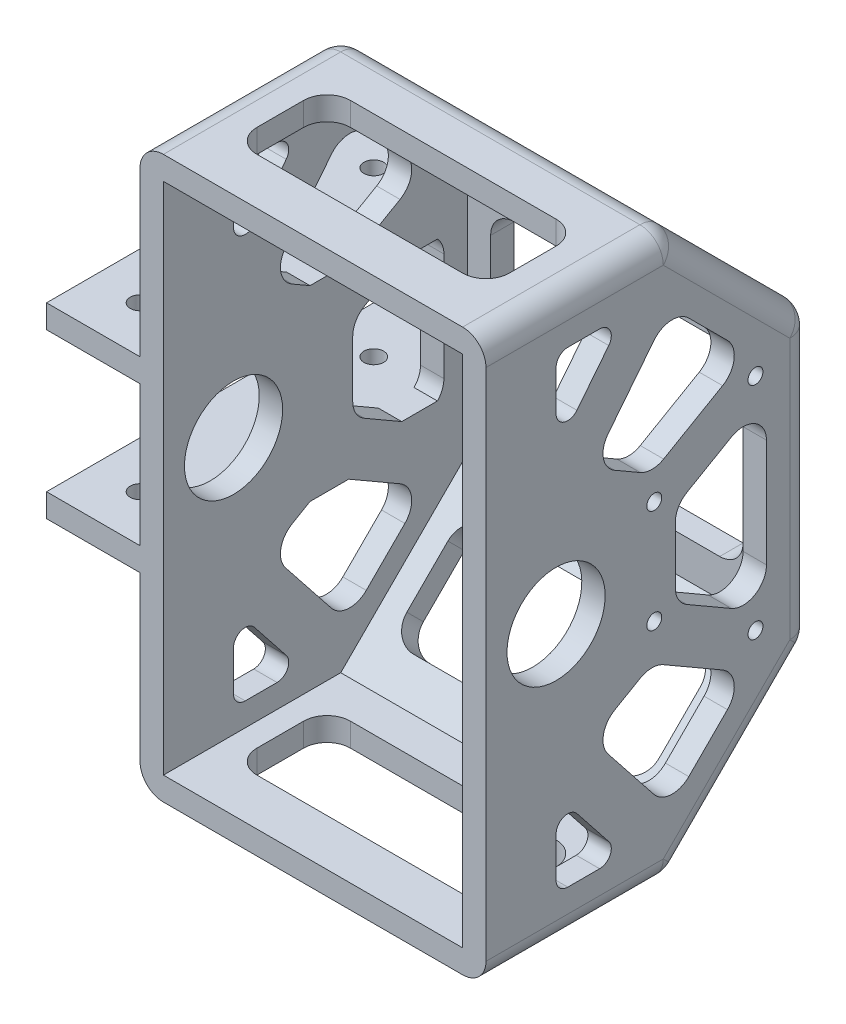
SolidWorks part; units mm, degrees
ref_plane "正面" through (0, 0, 0) normal (0, 0, 1) x (1, 0, 0)
ref_plane "平面" through (0, 0, 0) normal (0, 1, 0) x (1, 0, 0)
ref_plane "右側面" through (0, 0, 0) normal (1, 0, 0) x (0, 0, -1)
sketch "ｽｹｯﾁ1" plane through (0, 0, 0) normal (0, 0, 1) x (1, 0, 0)
  line L1 (-37, 60) -> (37, 60)
  line L2 (-37, 60) -> (-37, -60)
  line L3 (-37, -60) -> (37, -60)
  line L4 (37, 60) -> (37, -60)
  line L5 (-37, 60) -> (37, -60) construction
  line L6 (-37, -60) -> (37, 60) construction
  point P0 (0, 0)
  dimension "D1" = 120
  dimension "D2" = 74
extrude "ﾎﾞｽ - 押し出し1" add sketch "ｽｹｯﾁ1" along normal blind 70
chamfer "面取り2" distance 30 angle 45 2 edges at (0, 60, 0) (0, -60, 0)
sketch "ｽｹｯﾁ2" plane through (-37, 0, 0) normal (-1, 0, 0) x (0, 0, 1)
  line L0 (70, 60) -> (70, -60) construction
  line L1 (55, -23.6714) -> (55, -60)
  line L2 (55, 23.6714) -> (34.5, 11.8357)
  line L3 (34.5, 11.8357) -> (34.5, -11.8357)
  line L4 (34.5, -11.8357) -> (55, -23.6714)
  line L5 (55, -23.6714) -> (75.5, -11.8357)
  line L6 (75.5, -11.8357) -> (75.5, 11.8357)
  line L7 (75.5, 11.8357) -> (55, 23.6714)
  line L8 (70, -60) -> (30, -60) construction
  line L9 (34.5, -11.8357) -> (1.1122, -31.1122)
  line L11 (0, -30) -> (30, -60) construction
  line L12 (55, 23.6714) -> (55, 60)
  line L13 (70, 60) -> (30, 60) construction
  line L14 (34.5, 11.8357) -> (1.1122, 31.1122)
  line L15 (30, 60) -> (0, 30) construction
  line L16 (32, -16.1658) -> (52.5, -28.0015)
  line L17 (32, -7.5056) -> (-1.3878, -26.782)
  line L18 (57.5, -28.0015) -> (80.5, -14.7224)
  line L19 (80.5, -14.7224) -> (80.5, 14.7224)
  line L20 (80.5, 14.7224) -> (57.5, 28.0015)
  line L21 (29.5, 11.8357) -> (29.5, -11.8357)
  line L22 (37, 16.1658) -> (3.6122, 35.4423)
  line L23 (52.5, 28.0015) -> (32, 16.1658)
  line L24 (60, 23.6714) -> (60, 60)
  line L25 (60, -23.6714) -> (60, -60)
  line L26 (37, -7.5056) -> (57.5, -19.3412)
  line L27 (37, -16.1658) -> (3.6122, -35.4423)
  line L28 (52.5, -19.3412) -> (70.5, -8.9489)
  line L29 (70.5, -8.9489) -> (70.5, 8.9489)
  line L30 (70.5, 8.9489) -> (52.5, 19.3412)
  line L31 (39.5, 11.8357) -> (39.5, -11.8357)
  line L32 (32, 7.5056) -> (-1.3878, 26.782)
  line L33 (57.5, 19.3412) -> (37, 7.5056)
  line L35 (55, -23.6714) -> (34.1421, -50)
  line L36 (51.0808, -20.5665) -> (30.2229, -46.8952)
  line L37 (55, 23.6714) -> (34.1421, 50)
  line L38 (58.9192, 26.7762) -> (38.0613, 53.1048)
  line L39 (58.9192, -26.7762) -> (38.0613, -53.1048)
  line L40 (51.0808, 20.5665) -> (30.2229, 46.8952)
  line L47 (60, 50) -> (34.1421, 50)
  line L48 (34.1421, 50) -> (10, 25.8579)
  line L49 (10, 25.8579) -> (10, -25.8579)
  line L50 (10, -25.8579) -> (34.1421, -50)
  line L51 (34.1421, -50) -> (60, -50)
  line L52 (60, -50) -> (60, 50)
  line L53 (60, 50) -> (34.1421, 50)
  line L54 (34.1421, 50) -> (10, 25.8579)
  line L55 (10, 25.8579) -> (10, -25.8579)
  line L56 (10, -25.8579) -> (34.1421, -50)
  line L57 (34.1421, -50) -> (60, -50)
  line L58 (60, -50) -> (60, 50)
  circle A0 centre (55, 0) radius 10.5
  circle A1 centre (55, 0) radius 20.5 construction
  dimension "D1" = 21
  dimension "D2" = 15
  dimension "D3" = 41
  dimension "D4" = 5
  dimension "D5" = 5
  dimension "D6" = 10
  dimension "D7" = 5
  dimension "D8" = 5
shell "ｼｪﾙ1" thickness 5
extrude "ｶｯﾄ - 押し出し1" cut sketch "ｽｹｯﾁ2" against normal through all
sketch "ｽｹｯﾁ3" plane through (0, -15, -15) normal (0, -0.7071, -0.7071) x (1, 0, 0)
  line L8 (-27, 53.6396) -> (-27, 31.2132)
  line L9 (-27, 31.2132) -> (27, 31.2132)
  line L10 (27, 31.2132) -> (27, 53.6396)
  line L11 (27, 53.6396) -> (-27, 53.6396)
  line L12 (-27, 53.6396) -> (-27, 31.2132)
  line L13 (-27, 31.2132) -> (27, 31.2132)
  line L14 (27, 31.2132) -> (27, 53.6396)
  line L15 (27, 53.6396) -> (-27, 53.6396)
  dimension "D1" = 10
extrude "ｶｯﾄ - 押し出し2" cut sketch "ｽｹｯﾁ3" against normal blind 70
sketch "ｽｹｯﾁ4" plane through (0, 15, -15) normal (0, 0.7071, -0.7071) x (1, 0, 0)
  line L8 (27, -53.6396) -> (27, -31.2132)
  line L9 (27, -31.2132) -> (-27, -31.2132)
  line L10 (-27, -31.2132) -> (-27, -53.6396)
  line L11 (-27, -53.6396) -> (27, -53.6396)
  line L12 (27, -53.6396) -> (27, -31.2132)
  line L13 (27, -31.2132) -> (-27, -31.2132)
  line L14 (-27, -31.2132) -> (-27, -53.6396)
  line L15 (-27, -53.6396) -> (27, -53.6396)
  dimension "D1" = 10
extrude "ｶｯﾄ - 押し出し3" cut sketch "ｽｹｯﾁ4" against normal blind 70
sketch "ｽｹｯﾁ5" plane through (0, 0, 0) normal (0, 0, -1) x (-1, 0, 0)
  line L8 (27, -20) -> (27, 20)
  line L9 (27, 20) -> (-27, 20)
  line L10 (-27, 20) -> (-27, -20)
  line L11 (-27, -20) -> (27, -20)
  line L12 (27, -20) -> (27, 20)
  line L13 (27, 20) -> (-27, 20)
  line L14 (-27, 20) -> (-27, -20)
  line L15 (-27, -20) -> (27, -20)
  dimension "D1" = 10
extrude "ｶｯﾄ - 押し出し4" cut sketch "ｽｹｯﾁ5" against normal blind 70
sketch "ｽｹｯﾁ7" plane through (0, 60, 0) normal (0, 1, 0) x (1, 0, 0)
  line L8 (27, -60) -> (27, -40)
  line L9 (27, -40) -> (-27, -40)
  line L10 (-27, -40) -> (-27, -60)
  line L11 (-27, -60) -> (27, -60)
  line L12 (27, -60) -> (27, -40)
  line L13 (27, -40) -> (-27, -40)
  line L14 (-27, -40) -> (-27, -60)
  line L15 (-27, -60) -> (27, -60)
  dimension "D1" = 10
extrude "ｶｯﾄ - 押し出し5" cut sketch "ｽｹｯﾁ7" against normal through all
fillet "ﾌｨﾚｯﾄ1" radius 5 58 edges at (27, 51.1612, 24.6967) (-27, 51.1612, 24.6967) (-27, 35.3033, 8.8388) (27, 35.3033, 8.8388) (-27, 20, 2.5) (-27, -20, 2.5) (27, 20, 2.5) (27, -20, 2.5) (-27, -35.3033, 8.8388) (-27, -51.1612, 24.6967) (27, -51.1612, 24.6967) (27, -35.3033, 8.8388) (34.5, -29.596, 13.7382) (34.5, -17.6092, 34.5) (34.5, 17.6092, 34.5) (34.5, 29.596, 13.7382) (34.5, -20.2073, 10) (34.5, -8.9489, 29.5) (34.5, 8.9489, 29.5) (34.5, 20.2073, 10) (-34.5, 29.596, 13.7382) (-34.5, 17.6092, 34.5) (-34.5, 20.2073, 10) (-34.5, 8.9489, 29.5) (-34.5, -20.2073, 10) (-34.5, -8.9489, 29.5) (-34.5, -29.596, 13.7382) (-34.5, -17.6092, 34.5) (-27, -57.5, 60) (-27, -57.5, 40) (27, -57.5, 40) (27, -57.5, 60) (27, 57.5, 60) (27, 57.5, 40) (-27, 57.5, 40) (-27, 57.5, 60) (37, -45, 15) (37, -60, 50) (-37, -60, 50) (-37, -45, 15) (0, -30, 0) (-37, 0, 0) (-37, 45, 15) (0, 60, 30) (-37, 60, 50) (37, 60, 50) (0, 30, 0) (37, 45, 15) (37, 0, 0) (0, -60, 30) (34.5, -46.4408, 30.5829) (34.5, -25.1059, 47.4847) (34.5, 46.4408, 30.5829) (34.5, 25.1059, 47.4847) (-34.5, 46.4408, 30.5829) (-34.5, 25.1059, 47.4847) (-34.5, -25.1059, 47.4847) (-34.5, -46.4408, 30.5829)
sketch "ｽｹｯﾁ10" plane through (-37, 0, 0) normal (-1, 0, 0) x (0, 0, 1)
  line L0 (5, 27.9289) -> (5, -27.9289) construction
  line L1 (70, 17.5) -> (5, 17.5)
  line L2 (70, 17.5) -> (70, -17.5)
  line L3 (70, -17.5) -> (5, -17.5)
  line L4 (5, 17.5) -> (5, -17.5)
  line L5 (70, 17.5) -> (5, -17.5) construction
  line L6 (70, -17.5) -> (5, 17.5) construction
  line L7 (70, 55) -> (70, -55) construction
  line L8 (70, -15) -> (5, -15)
  line L9 (70, 20) -> (5, 20)
  line L10 (70, -20) -> (5, -20)
  line L11 (70, 15) -> (5, 15)
  line L13 (5, -15) -> (0, -15)
  line L14 (5, -15) -> (5, -20)
  line L15 (5, -20) -> (0, -20)
  line L16 (0, -15) -> (0, -20)
  line L17 (2.5, -20) -> (2.5, -15) construction
  line L18 (5, -17.5) -> (0, -17.5) construction
  line L19 (5, 20) -> (0, 20)
  line L20 (5, 20) -> (5, 15)
  line L21 (5, 15) -> (0, 15)
  line L22 (0, 20) -> (0, 15)
  line L23 (2.5, 15) -> (2.5, 20) construction
  line L24 (5, 17.5) -> (0, 17.5) construction
  circle A0 centre (55, 0) radius 10.5 construction
  point P0 (37.5, 0)
  point P110 (2.5, -17.5)
  point P114 (2.5, 17.5)
  line M12 (42.4694, 22.2103) -> (37, 19.0526)
  arc M13 (37, 19.0526) -> (32, 19.0526) centre (34.5, 23.3827) cw
  line M14 (32, 19.0526) -> (19.3813, 26.338)
  arc M17 (10, 11.547) -> (17.5, 15.8771) centre (15, 11.547) cw
  line M18 (17.5, 15.8771) -> (27, 10.3923)
  line M22 (27, -10.3923) -> (17.5, -15.8771)
  arc M23 (17.5, -15.8771) -> (10, -11.547) centre (15, -11.547) cw
  line M28 (19.3813, -26.338) -> (32, -19.0526)
  arc M29 (32, -19.0526) -> (37, -19.0526) centre (34.5, -23.3827) cw
  line M30 (37, -19.0526) -> (42.4694, -22.2103)
  line M36 (70, -55) -> (70, 55)
  line M39 (5, 27.9289) -> (5, -27.9289)
  dimension "D1" = 0
  dimension "D2" = 35
  dimension "D3" = 0
  dimension "D4" = 2.5
  dimension "D5" = 2.5
extrude "ﾎﾞｽ - 押し出し3" add sketch "ｽｹｯﾁ10" along normal blind 20 and the other way blind 5 contours L8 L4 L3 M36 M22 M23 | L10 L3 M36 M39 M28 M29 M30 | L11 L1 M36 M39 M17 M18 | L9 L1 M36 M12 M13 M14 M39 | L10 M30 M29 M28 | L9 M12 M14 M13 | L8 M22 M23 | L11 M18 M17 | L19 L22 L21 M39 | L13 L16 L15 L4 M39
sketch "ｽｹｯﾁ12" plane through (0, -20, 0) normal (0, -1, 0) x (1, 0, 0)
  line L0 (-57, 70) -> (-57, 0) construction
  line L1 (-37, 70) -> (-57, 70) construction
  line L2 (-57, 70) -> (-57, 0) construction
  circle A0 centre (-47, 60) radius 2.1
  circle A1 centre (-47, 10) radius 2.1
  dimension "D1" = 10
  dimension "D2" = 10
  dimension "D3" = 4.2
  dimension "D4" = 50
  dimension "D5" = 4.2
  dimension "D6" = 10
extrude "ｶｯﾄ - 押し出し7" cut sketch "ｽｹｯﾁ12" against normal through all
sketch "ｽｹｯﾁ13" plane through (37, 0, 0) normal (1, 0, 0) x (0, 0, -1)
  circle A0 centre (-12.3494, 24.6244) radius 1.6
  circle A1 centre (-34, 12.1244) radius 1.6
  circle A2 centre (-34, -10.0111) radius 1.6
  circle A3 centre (-12.3494, -22.5111) radius 1.6
extrude "ｶｯﾄ - 押し出し8" cut sketch "ｽｹｯﾁ13" against normal blind 10
fillet "ﾌｨﾚｯﾄ2" radius 2.5 12 edges at (34.5, -50, 40.521) (34.5, -50, 55) (34.5, -31.7233, 55) (34.5, 31.7233, 55) (34.5, 50, 40.521) (34.5, 50, 55) (-34.5, 50, 55) (-34.5, 50, 40.521) (-34.5, 31.7233, 55) (-34.5, -31.7233, 55) (-34.5, -50, 40.521) (-34.5, -50, 55)
